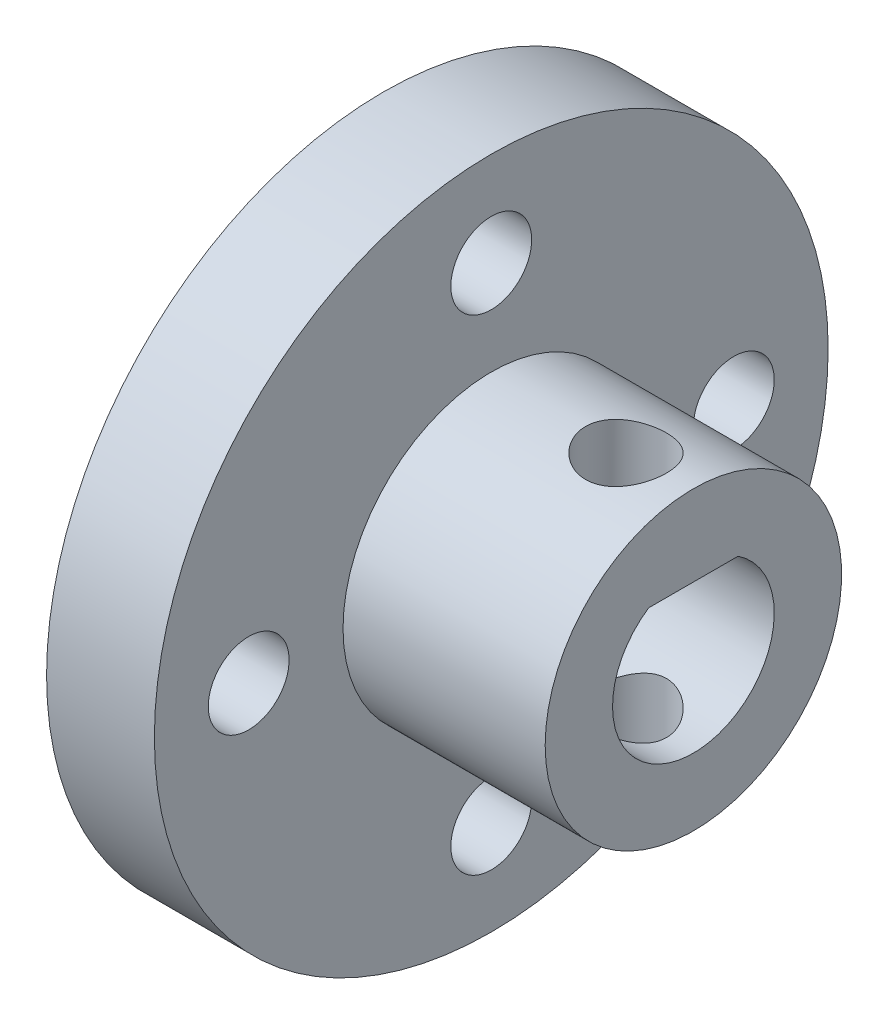
SolidWorks part; units mm, degrees
ref_plane "前视基准面" through (0, 0, 0) normal (0, 0, 1) x (1, 0, 0)
ref_plane "上视基准面" through (0, 0, 0) normal (0, 1, 0) x (1, 0, 0)
ref_plane "右视基准面" through (0, 0, 0) normal (1, 0, 0) x (0, 0, -1)
sketch "草图4" plane through (0, 0, 0) normal (0, 0, 1) x (1, 0, 0)
  line L0 (0, 0) -> (0, 12.5)
  line L1 (0, 12.5) -> (4, 12.5)
  line L2 (4, 12.5) -> (4, 5.5)
  line L3 (4, 5.5) -> (11.5, 5.5)
  line L4 (0, 0) -> (11.5, 0)
  line L5 (11.5, 5.5) -> (11.5, 0)
revolve "旋转1" add sketch "草图4" angle 360 about L4
sketch "草图5" plane through (11.5, 0, 0) normal (1, 0, 0) x (0, 0, -1)
  line L1 (-1.6583, 2.5) -> (1.6583, 2.5)
  arc A0 (-1.6583, 2.5) -> (1.6583, 2.5) centre (0, 0) ccw
extrude "切除-拉伸1" cut sketch "草图5" against normal up to next
ref_plane "基准面1" through (0, 6.5, 0) normal (0, 1, 0) x (1, 0, 0)
sketch "草图7" plane through (0, 6.5, 0) normal (0, 1, 0) x (1, 0, 0)
  circle A0 centre (9, 0) radius 1.5
extrude "切除-拉伸2" cut sketch "草图7" against normal blind 16
sketch "草图8" plane through (0, 0, 0) normal (-1, 0, 0) x (0, 0, 1)
  circle A1 centre (9, 0) radius 1.5
  circle A2 centre (0, -9) radius 1.5
  circle A3 centre (-9, 0) radius 1.5
  circle A4 centre (0, 9) radius 1.5
  point P13 (0, 0)
  dimension "D1" = 4
extrude "切除-拉伸3" cut sketch "草图8" against normal up to next
